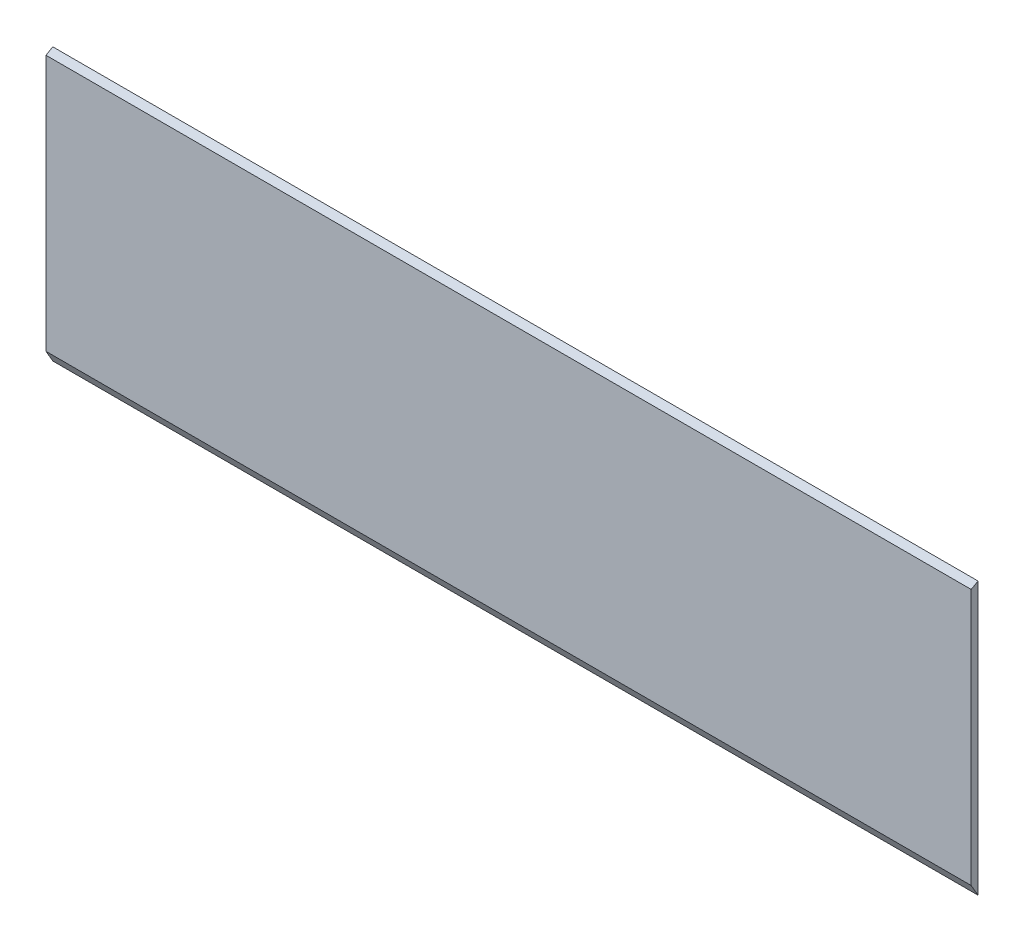
SolidWorks part; units mm, degrees
ref_plane "Front Plane" through (0, 0, 0) normal (0, 0, 1) x (1, 0, 0)
ref_plane "Top Plane" through (0, 0, 0) normal (0, 1, 0) x (1, 0, 0)
ref_plane "Right Plane" through (0, 0, 0) normal (1, 0, 0) x (0, 0, -1)
sketch "Sketch2" plane through (0, 0, 0) normal (0, 0, 1) x (1, 0, 0)
  line L1 (0, 0) -> (431.8, 0)
  line L2 (0, 0) -> (0, 127)
  line L3 (0, 127) -> (431.8, 127)
  line L4 (431.8, 0) -> (431.8, 127)
  dimension "D1" = 431.8
  dimension "D2" = 127
extrude "Boss-Extrude1" add sketch "Sketch2" along normal blind 3.175
sketch "Sketch3" plane through (0, 0, 0) normal (-1, 0, 0) x (0, 0, 1)
  line L0 (0, 0) -> (3.175, 5.4993)
  line L2 (3.175, 127) -> (3.175, 0) construction
  line L3 (3.175, 0) -> (0, 0) construction
  dimension "D1" = 60
extrude "Cut-Extrude1" cut sketch "Sketch3" against normal through all and the other way through all flip side to cut
sketch "Sketch4" plane through (431.8, 0, 0) normal (1, 0, 0) x (0, 0, -1)
  line L0 (0, 127) -> (-3.175, 125.1669)
  line L1 (-3.175, 5.4993) -> (-3.175, 127) construction
  line L2 (-3.175, 127) -> (0, 127) construction
  dimension "D1" = 30
extrude "Cut-Extrude2" cut sketch "Sketch4" against normal through all and the other way through all flip side to cut
